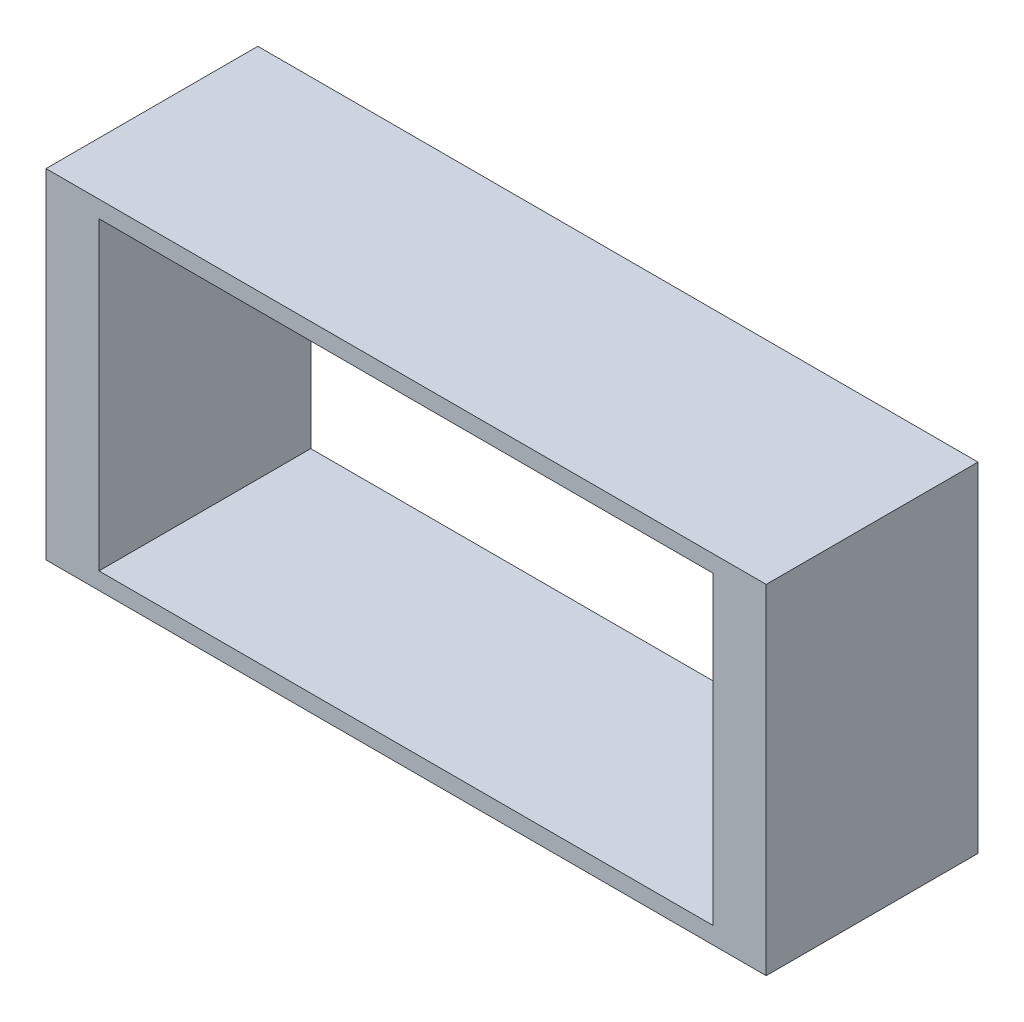
SolidWorks part; units mm, degrees
ref_plane "Front Plane" through (0, 0, 0) normal (0, 0, 1) x (1, 0, 0)
ref_plane "Top Plane" through (0, 0, 0) normal (0, 1, 0) x (1, 0, 0)
ref_plane "Right Plane" through (0, 0, 0) normal (1, 0, 0) x (0, 0, -1)
sketch "Sketch2" plane through (0, 0, 0) normal (0, 0, 1) x (1, 0, 0)
  line L1 (0, 0) -> (34, 0)
  line L2 (0, 0) -> (0, -16)
  line L3 (0, -16) -> (34, -16)
  line L4 (34, 0) -> (34, -16)
  line L5 (2.5, -0.8) -> (31.5, -0.8)
  line L6 (2.5, -0.8) -> (2.5, -15.2)
  line L7 (2.5, -15.2) -> (31.5, -15.2)
  line L8 (31.5, -0.8) -> (31.5, -15.2)
  dimension "D1" = 16
  dimension "D2" = 34
  dimension "D3" = 29
  dimension "D4" = 14.4
  dimension "D5" = 2.5
  dimension "D6" = 0.8
extrude "Boss-Extrude3" add sketch "Sketch2" along normal blind 10
